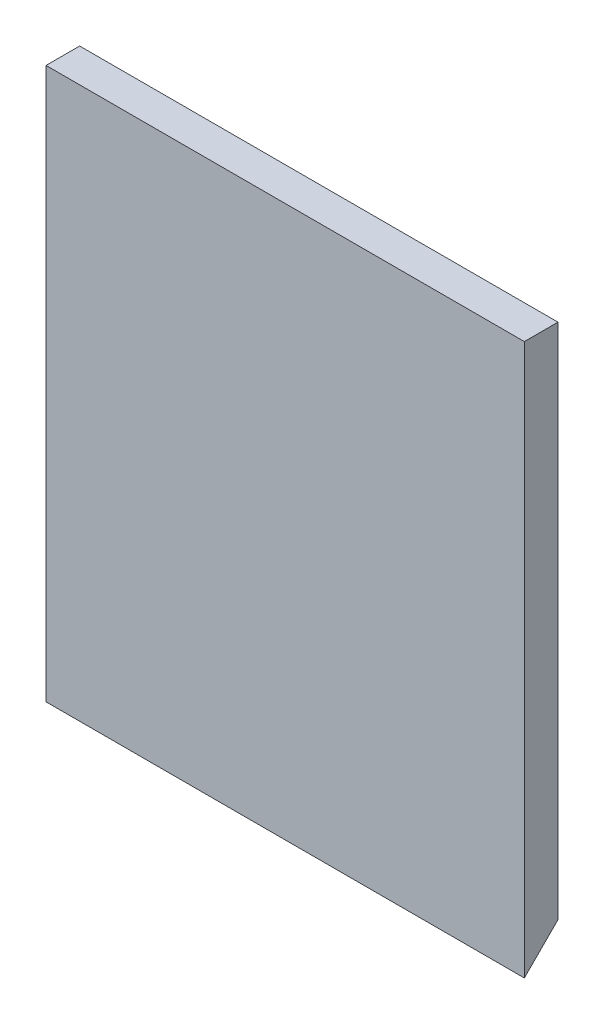
SolidWorks part; units mm, degrees
ref_plane "Plan de face" through (0, 0, 0) normal (0, 0, 1) x (1, 0, 0)
ref_plane "Plan de dessus" through (0, 0, 0) normal (0, 1, 0) x (1, 0, 0)
ref_plane "Plan de droite" through (0, 0, 0) normal (1, 0, 0) x (0, 0, -1)
sketch "Esquisse1" plane through (0, 0, 0) normal (0, 0, 1) x (1, 0, 0)
  line L0 (-128, 0) -> (128, 0)
  line L1 (128, 0) -> (128, 295)
  line L2 (128, 295) -> (-128, 295)
  line L3 (0, 0) -> (0, 295) construction
  line L4 (-128, 0) -> (-128, 295)
  dimension "D1" = 256
  dimension "D3" = 295
extrude "Boss.-Extru.1" add sketch "Esquisse1" along normal blind 18
sketch "Esquisse2" plane through (128, 0, 0) normal (1, 0, 0) x (0, 0, -1)
  line L0 (-18, 0) -> (0, 18)
  line L1 (0, 0) -> (0, 295) construction
  line L2 (0, 18) -> (0, 0)
  line L3 (0, 0) -> (-18, 0)
  dimension "D1" = 45
extrude "Enlèv. mat.-Extru.1" cut sketch "Esquisse2" against normal through all both and the other way through all
